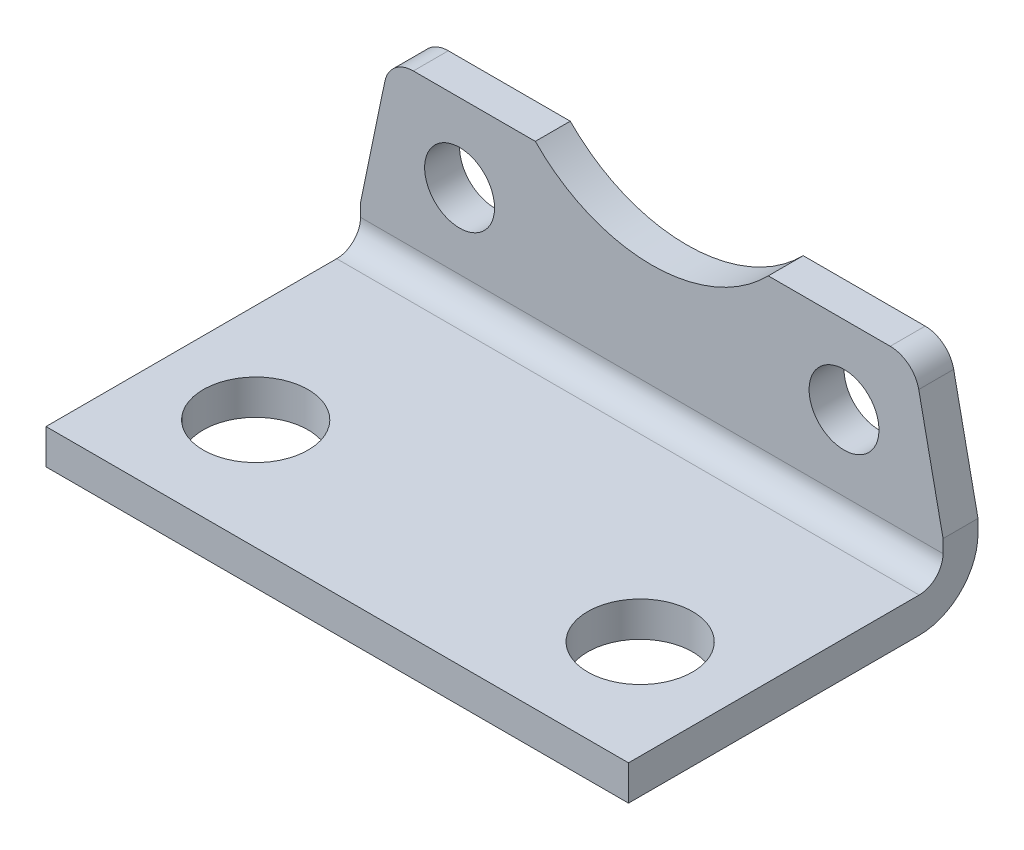
SolidWorks part; units mm, degrees
ref_plane "前视基准面" through (0, 0, 0) normal (0, 0, 1) x (1, 0, 0)
ref_plane "上视基准面" through (0, 0, 0) normal (0, 1, 0) x (1, 0, 0)
ref_plane "右视基准面" through (0, 0, 0) normal (1, 0, 0) x (0, 0, -1)
sketch "草图1" plane through (0, 0, 0) normal (1, 0, 0) x (0, 0, -1)
  line L0 (0, 0) -> (0, 28) construction
  line L1 (-76.5, 0) -> (76.5, 0) construction
  line L2 (-67, 0) -> (-67, 3) construction
  point P7 (-62.5, 0)
  point P8 (-46.5, 0)
  dimension "AH" = 28
  dimension "AA" = 153
  dimension "AD" = 9.5
  dimension "AT" = 3
  dimension "AP" = 9
  dimension "AG" = 20.5
sketch "草图2" plane through (0, 0, 0) normal (0, 0, 1) x (1, 0, 0)
  line L0 (-25, 0) -> (25, 0) construction
  line L1 (0, 0) -> (0, 14) construction
  line L2 (0, 0) -> (0, 28) construction
  line L4 (-16.5, 11.5) -> (16.5, 11.5)
  line L5 (-16.5, 11.5) -> (-16.5, 44.5)
  line L6 (-16.5, 44.5) -> (16.5, 44.5)
  line L7 (16.5, 11.5) -> (16.5, 44.5)
  line L8 (-16.5, 11.5) -> (16.5, 44.5) construction
  line L9 (-16.5, 44.5) -> (16.5, 11.5) construction
  line L10 (-22.5, 5.5) -> (22.5, 5.5)
  line L11 (-22.5, 5.5) -> (-22.5, 50.5)
  line L12 (-22.5, 50.5) -> (22.5, 50.5)
  line L13 (22.5, 5.5) -> (22.5, 50.5)
  line L14 (-22.5, 5.5) -> (22.5, 50.5) construction
  line L15 (-22.5, 50.5) -> (22.5, 5.5) construction
  circle A0 centre (-16.5, 11.5) radius 3
  circle A1 centre (0, 28) radius 14
  point P7 (-16.5, 0)
  point P9 (0, 28)
  dimension "D1" = 45
  dimension "L" = 6
  dimension "D" = 28
  dimension "AE" = 50
  dimension "AF" = 33
  dimension "T" = 33
sketch "草图3" plane through (0, 0, 0) normal (1, 0, 0) x (0, 0, -1)
  line L0 (-76.5, 0) -> (-76.5, 3)
  line L1 (-76.5, 3) -> (-51.55, 3)
  line L2 (-49.5, 5.05) -> (-49.5, 28)
  line L3 (-46.5, 5.05) -> (-46.5, 28)
  line L4 (-46.5, 28) -> (-49.5, 28)
  line L5 (-76.5, 0) -> (-51.55, 0)
  arc A0 (-51.55, 3) -> (-49.5, 5.05) centre (-51.55, 5.05) ccw
  arc A1 (-51.55, 0) -> (-46.5, 5.05) centre (-51.55, 5.05) ccw
  dimension "D1" = 4.1
extrude "凸台-拉伸1" add sketch "草图3" against normal up to vertex (25 mm away) from vertex at 25 starting at point (25, 0, 0)
sketch "草图4" plane through (0, 3, 0) normal (0, 1, 0) x (1, 0, 0)
  circle A0 centre (-16.5, -67) radius 4.5
  point P2 (-16.5, -62.5)
extrude "切除-拉伸1" cut sketch "草图4" against normal through all
mirror "镜向1" about plane through (0, 0, 0) normal (1, 0, 0) of "切除-拉伸1"
sketch "草图6" plane through (0, 0, 49.5) normal (0, 0, 1) x (1, 0, 0)
  circle A0 centre (-16.5, 11.5) radius 3 construction
  circle A1 centre (-16.5, 11.5) radius 3
extrude "切除-拉伸2" cut sketch "草图6" against normal through all
mirror "镜向2" about plane through (0, 0, 0) normal (1, 0, 0) of "切除-拉伸2"
sketch "草图7" plane through (0, 0, 49.5) normal (0, 0, 1) x (1, 0, 0)
  circle A0 centre (0, 28) radius 14 construction
  circle A1 centre (0, 28) radius 14
extrude "切除-拉伸3" cut sketch "草图7" against normal through all
sketch "草图9" plane through (0, 0, 49.5) normal (0, 0, 1) x (1, 0, 0)
  line L0 (-25, 18.2) -> (25, 18.2)
  line L1 (-25, 28) -> (-25, 5.05) construction
  line L2 (-25, 18.2) -> (-25, 28)
  line L3 (-25, 28) -> (25, 28)
  line L4 (25, 28) -> (25, 18.2)
  dimension "D1" = 9.8
extrude "切除-拉伸4" cut sketch "草图9" against normal through all
sketch "草图8" plane through (0, 0, 49.5) normal (0, 0, 1) x (1, 0, 0)
  line L0 (-22.5, 18.2) -> (22.5, 18.2)
  line L1 (-25, 18.2) -> (-25, 5.05) construction
  line L2 (0, 0) -> (0, 28) construction
  line L3 (-22.5, 5.5) -> (-22.5, 50.5) construction
  line L4 (-22.5, 18.2) -> (-25, 6.17)
  line L5 (22.5, 18.2) -> (25, 6.17)
  line L6 (-25, 6.17) -> (-25, 28)
  line L7 (-25, 28) -> (25, 28)
  line L8 (25, 28) -> (25, 6.17)
  line L9 (25, 18.2) -> (25, 5.05) construction
  dimension "D1" = 9.8
  dimension "D2" = 1.12
  dimension "D3" = 1.12
extrude "压缩" cut sketch "草图8" against normal through all
fillet "圆角1" radius 2.5 2 edges at (22.5, 18.2, 48) (-22.5, 18.2, 48)
equation "\"D1@草图3\" = \"AG@草图1\"*0.2"
equation "\"D1@草图8\" = \"D@草图2\"/2*0.7"
equation "\"D1@圆角1\" = \"AE@草图2\"*0.05"
equation "\"D2@草图8\" = \"AH@草图1\"*0.04"
equation "\"D3@草图8\" = \"D2@草图8\""
equation "\"D1@草图9\" = \"D@草图2\"/2*0.7"
